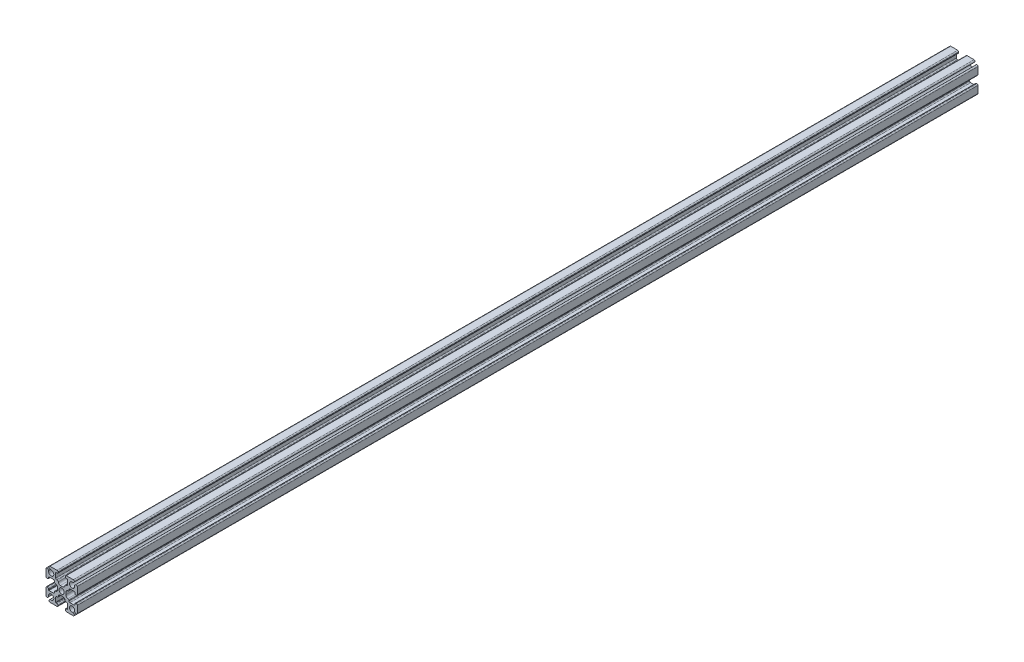
SolidWorks part; units mm, degrees
material "6063-T5"
ref_plane "Front Plane" through (0, 0, 0) normal (0, 0, 1) x (1, 0, 0)
ref_plane "Top Plane" through (0, 0, 0) normal (0, 1, 0) x (1, 0, 0)
ref_plane "Right Plane" through (0, 0, 0) normal (1, 0, 0) x (0, 0, -1)
sketch "Sketch1" plane through (0, 0, 0) normal (0, 0, 1) x (1, 0, 0)
  line L0 (6.6464, 5.9393) -> (6.1636, 5.4565)
  line L1 (5.4565, 6.1636) -> (5.9393, 6.6464)
  line L2 (5.5858, 7.5) -> (2.25, 7.5)
  line L3 (1.75, 7) -> (1.75, 6.8)
  line L4 (2.25, 6.3) -> (2.65, 6.3)
  line L5 (2.85, 6.1) -> (2.85, 4)
  line L6 (2.35, 3.5) -> (2.1, 3.5)
  line L7 (0.6, 2) -> (-0.6, 2)
  line L8 (-2.1, 3.5) -> (-2.35, 3.5)
  line L9 (-2.85, 4) -> (-2.85, 6.1)
  line L10 (-2.65, 6.3) -> (-2.25, 6.3)
  line L11 (-1.75, 6.8) -> (-1.75, 7)
  line L12 (-2.25, 7.5) -> (-5.5858, 7.5)
  line L13 (-5.9393, 6.6464) -> (-5.4565, 6.1636)
  line L14 (-6.1636, 5.4565) -> (-6.6464, 5.9393)
  line L15 (-7.5, 5.5858) -> (-7.5, 2.25)
  line L16 (-7, 1.75) -> (-6.8, 1.75)
  line L17 (-6.3, 2.25) -> (-6.3, 2.65)
  line L18 (-6.1, 2.85) -> (-4, 2.85)
  line L19 (-3.5, 2.35) -> (-3.5, 2.1)
  line L20 (-2, 0.6) -> (-2, -0.6)
  line L21 (-3.5, -2.1) -> (-3.5, -2.35)
  line L22 (-4, -2.85) -> (-6.1, -2.85)
  line L23 (-6.3, -2.65) -> (-6.3, -2.25)
  line L24 (-6.8, -1.75) -> (-7, -1.75)
  line L25 (-7.5, -2.25) -> (-7.5, -5.5858)
  line L26 (-6.6464, -5.9393) -> (-6.1636, -5.4565)
  line L27 (-5.4565, -6.1636) -> (-5.9393, -6.6464)
  line L28 (-5.5858, -7.5) -> (-2.25, -7.5)
  line L29 (-1.75, -7) -> (-1.75, -6.8)
  line L30 (-2.25, -6.3) -> (-2.65, -6.3)
  line L31 (-2.85, -6.1) -> (-2.85, -4)
  line L32 (-2.35, -3.5) -> (-2.1, -3.5)
  line L33 (-0.6, -2) -> (0.6, -2)
  line L34 (2.1, -3.5) -> (2.35, -3.5)
  line L35 (2.85, -4) -> (2.85, -6.1)
  line L36 (2.65, -6.3) -> (2.25, -6.3)
  line L37 (1.75, -6.8) -> (1.75, -7)
  line L38 (2.25, -7.5) -> (5.5858, -7.5)
  line L39 (5.9393, -6.6464) -> (5.4565, -6.1636)
  line L40 (6.1636, -5.4565) -> (6.6464, -5.9393)
  line L41 (7.5, -5.5858) -> (7.5, -2.25)
  line L42 (7, -1.75) -> (6.8, -1.75)
  line L43 (6.3, -2.25) -> (6.3, -2.65)
  line L44 (6.1, -2.85) -> (4, -2.85)
  line L45 (3.5, -2.35) -> (3.5, -2.1)
  line L46 (2, -0.6) -> (2, 0.6)
  line L47 (3.5, 2.1) -> (3.5, 2.35)
  line L48 (4, 2.85) -> (6.1, 2.85)
  line L49 (6.3, 2.65) -> (6.3, 2.25)
  line L50 (6.8, 1.75) -> (7, 1.75)
  line L51 (7.5, 2.25) -> (7.5, 5.5858)
  circle A0 centre (0, 0) radius 1.25
  arc A1 (6.1636, 5.4565) -> (5.4565, 6.1636) centre (5, 5) cw
  arc A2 (5.9393, 6.6464) -> (5.5858, 7.5) centre (5.5858, 7) ccw
  arc A3 (2.25, 7.5) -> (1.75, 7) centre (2.25, 7) ccw
  arc A4 (1.75, 6.8) -> (2.25, 6.3) centre (2.25, 6.8) ccw
  arc A5 (2.65, 6.3) -> (2.85, 6.1) centre (2.65, 6.1) cw
  arc A6 (2.85, 4) -> (2.35, 3.5) centre (2.35, 4) cw
  arc A7 (2.1, 3.5) -> (1.6, 3) centre (2.1, 3) ccw
  arc A8 (1.6, 3) -> (0.6, 2) centre (0.6, 3) cw
  arc A9 (-0.6, 2) -> (-1.6, 3) centre (-0.6, 3) cw
  arc A10 (-1.6, 3) -> (-2.1, 3.5) centre (-2.1, 3) ccw
  arc A11 (-2.35, 3.5) -> (-2.85, 4) centre (-2.35, 4) cw
  arc A12 (-2.85, 6.1) -> (-2.65, 6.3) centre (-2.65, 6.1) cw
  arc A13 (-2.25, 6.3) -> (-1.75, 6.8) centre (-2.25, 6.8) ccw
  arc A14 (-1.75, 7) -> (-2.25, 7.5) centre (-2.25, 7) ccw
  arc A15 (-5.5858, 7.5) -> (-5.9393, 6.6464) centre (-5.5858, 7) ccw
  arc A16 (-5.4565, 6.1636) -> (-6.1636, 5.4565) centre (-5, 5) cw
  arc A17 (-6.6464, 5.9393) -> (-7.5, 5.5858) centre (-7, 5.5858) ccw
  arc A18 (-7.5, 2.25) -> (-7, 1.75) centre (-7, 2.25) ccw
  arc A19 (-6.8, 1.75) -> (-6.3, 2.25) centre (-6.8, 2.25) ccw
  arc A20 (-6.3, 2.65) -> (-6.1, 2.85) centre (-6.1, 2.65) cw
  arc A21 (-4, 2.85) -> (-3.5, 2.35) centre (-4, 2.35) cw
  arc A22 (-3.5, 2.1) -> (-3, 1.6) centre (-3, 2.1) ccw
  arc A23 (-3, 1.6) -> (-2, 0.6) centre (-3, 0.6) cw
  arc A24 (-2, -0.6) -> (-3, -1.6) centre (-3, -0.6) cw
  arc A25 (-3, -1.6) -> (-3.5, -2.1) centre (-3, -2.1) ccw
  arc A26 (-3.5, -2.35) -> (-4, -2.85) centre (-4, -2.35) cw
  arc A27 (-6.1, -2.85) -> (-6.3, -2.65) centre (-6.1, -2.65) cw
  arc A28 (-6.3, -2.25) -> (-6.8, -1.75) centre (-6.8, -2.25) ccw
  arc A29 (-7, -1.75) -> (-7.5, -2.25) centre (-7, -2.25) ccw
  arc A30 (-7.5, -5.5858) -> (-6.6464, -5.9393) centre (-7, -5.5858) ccw
  arc A31 (-6.1636, -5.4565) -> (-5.4565, -6.1636) centre (-5, -5) cw
  arc A32 (-5.9393, -6.6464) -> (-5.5858, -7.5) centre (-5.5858, -7) ccw
  arc A33 (-2.25, -7.5) -> (-1.75, -7) centre (-2.25, -7) ccw
  arc A34 (-1.75, -6.8) -> (-2.25, -6.3) centre (-2.25, -6.8) ccw
  arc A35 (-2.65, -6.3) -> (-2.85, -6.1) centre (-2.65, -6.1) cw
  arc A36 (-2.85, -4) -> (-2.35, -3.5) centre (-2.35, -4) cw
  arc A37 (-2.1, -3.5) -> (-1.6, -3) centre (-2.1, -3) ccw
  arc A38 (-1.6, -3) -> (-0.6, -2) centre (-0.6, -3) cw
  arc A39 (0.6, -2) -> (1.6, -3) centre (0.6, -3) cw
  arc A40 (1.6, -3) -> (2.1, -3.5) centre (2.1, -3) ccw
  arc A41 (2.35, -3.5) -> (2.85, -4) centre (2.35, -4) cw
  arc A42 (2.85, -6.1) -> (2.65, -6.3) centre (2.65, -6.1) cw
  arc A43 (2.25, -6.3) -> (1.75, -6.8) centre (2.25, -6.8) ccw
  arc A44 (1.75, -7) -> (2.25, -7.5) centre (2.25, -7) ccw
  arc A45 (5.5858, -7.5) -> (5.9393, -6.6464) centre (5.5858, -7) ccw
  arc A46 (5.4565, -6.1636) -> (6.1636, -5.4565) centre (5, -5) cw
  arc A47 (6.6464, -5.9393) -> (7.5, -5.5858) centre (7, -5.5858) ccw
  arc A48 (7.5, -2.25) -> (7, -1.75) centre (7, -2.25) ccw
  arc A49 (6.8, -1.75) -> (6.3, -2.25) centre (6.8, -2.25) ccw
  arc A50 (6.3, -2.65) -> (6.1, -2.85) centre (6.1, -2.65) cw
  arc A51 (4, -2.85) -> (3.5, -2.35) centre (4, -2.35) cw
  arc A52 (3.5, -2.1) -> (3, -1.6) centre (3, -2.1) ccw
  arc A53 (3, -1.6) -> (2, -0.6) centre (3, -0.6) cw
  arc A54 (2, 0.6) -> (3, 1.6) centre (3, 0.6) cw
  arc A55 (3, 1.6) -> (3.5, 2.1) centre (3, 2.1) ccw
  arc A56 (3.5, 2.35) -> (4, 2.85) centre (4, 2.35) cw
  arc A57 (6.1, 2.85) -> (6.3, 2.65) centre (6.1, 2.65) cw
  arc A58 (6.3, 2.25) -> (6.8, 1.75) centre (6.8, 2.25) ccw
  arc A59 (7, 1.75) -> (7.5, 2.25) centre (7, 2.25) ccw
  arc A60 (7.5, 5.5858) -> (6.6464, 5.9393) centre (7, 5.5858) ccw
extrude "Boss-Extrude1" add sketch "Sketch1" along normal blind 432
